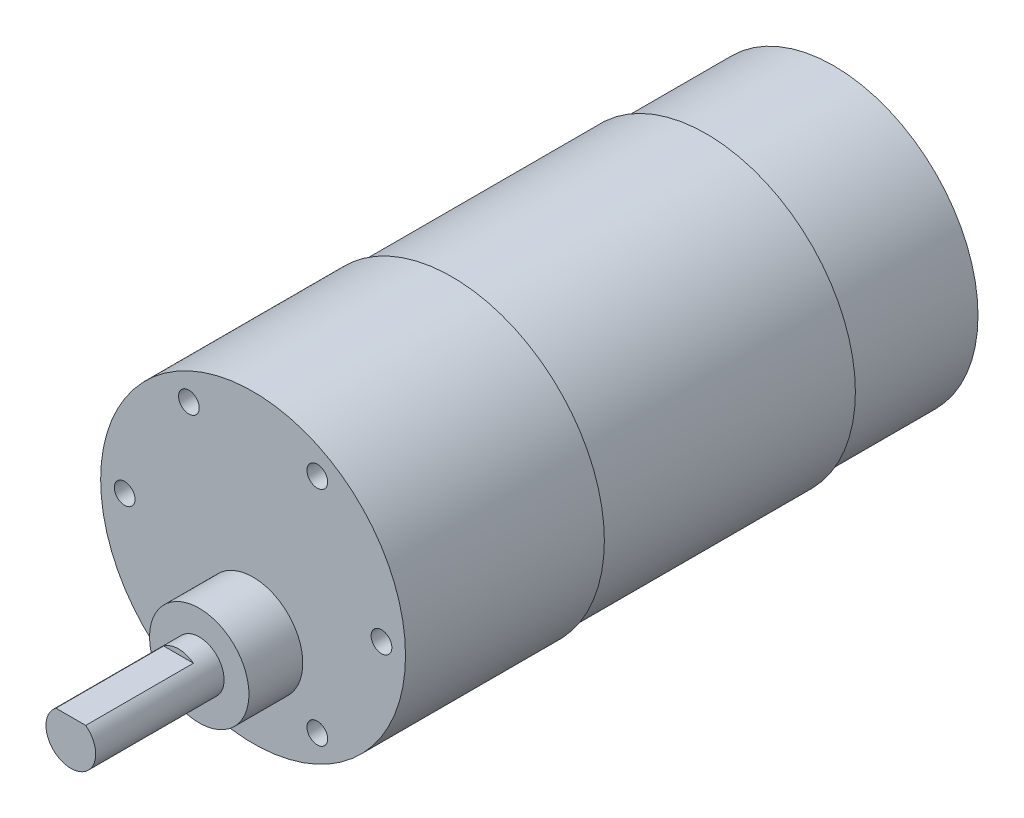
SolidWorks part; units mm, degrees
ref_plane "Front Plane" through (0, 0, 0) normal (0, 0, 1) x (1, 0, 0)
ref_plane "Top Plane" through (0, 0, 0) normal (0, 1, 0) x (1, 0, 0)
ref_plane "Right Plane" through (0, 0, 0) normal (1, 0, 0) x (0, 0, -1)
sketch "Sketch1" plane through (0, 0, 0) normal (0, 0, 1) x (1, 0, 0)
  circle A0 centre (0, 0) radius 17.4
  dimension "D1" = 34.8
extrude "Boss-Extrude1" add sketch "Sketch1" along normal blind 15.4
sketch "Sketch2" plane through (0, 0, 15.4) normal (0, 0, 1) x (1, 0, 0)
  circle A0 centre (0, 0) radius 18
  dimension "D1" = 36
extrude "Boss-Extrude2" add sketch "Sketch2" along normal blind 30.7
sketch "Sketch3" plane through (0, 0, 46.1) normal (0, 0, 1) x (1, 0, 0)
  circle A0 centre (0, 0) radius 18.4
  dimension "D1" = 36.8
extrude "Boss-Extrude3" add sketch "Sketch3" along normal blind 24
sketch "Sketch4" plane through (0, 0, 70.1) normal (0, 0, 1) x (1, 0, 0)
  circle A0 centre (0, -7) radius 6
  point P2 (0, 0)
  dimension "D2" = 12
  dimension "D1" = 7
extrude "Boss-Extrude4" add sketch "Sketch4" along normal blind 6.5
sketch "Sketch5" plane through (0, 0, 76.6) normal (0, 0, 1) x (1, 0, 0)
  circle A0 centre (0, -7) radius 3
  dimension "D1" = 6
extrude "Boss-Extrude5" add sketch "Sketch5" along normal blind 15.5
sketch "Sketch6" plane through (0, 0, 92.1) normal (0, 0, 1) x (1, 0, 0)
  line L0 (-1.8, -4.6) -> (1.8, -4.6)
  circle A0 centre (0, -7) radius 3 construction
  circle A1 centre (0, -7) radius 3 construction
  arc A2 (-1.8, -4.6) -> (1.8, -4.6) centre (0, -7) cw
  dimension "D1" = 2.4
extrude "Cut-Extrude1" cut sketch "Sketch6" against normal blind 13
hole_wizard "Tap Drill for M3x0.5 Tap1" positions "Sketch7" profile "Sketch8" hole size "M3x0.5" standard "ANSI Metric"
sketch "Sketch7" plane through (0, 0, 70.1) normal (0, 0, 1) x (1, 0, 0)
  circle A0 centre (0, 0) radius 15.5
  point P0 (-15.5, 0)
  point P13 (-7.75, 13.4234)
  point P14 (7.75, 13.4234)
  point P15 (15.5, 0)
  point P16 (7.75, -13.4234)
  point P17 (-7.75, -13.4234)
  point P24 (0, 0)
  point P25 (0, 0)
  dimension "D1" = 15.5
  dimension "D2" = 6
sketch "Sketch8" plane through (-15.5, 0, 70.1) normal (1, 0, 0) x (0, -1, 0)
  line L0 (0, 0) -> (0, 10.76)
  line L1 (0, 10.76) -> (1.25, 10.76)
  line L2 (1.25, 10.76) -> (1.25, 0)
  line L5 (1.25, 0) -> (0, 0)
  line L10 (0, 10.76) -> (-1.25, 10.76) construction
  line L11 (0, -6.35) -> (0, 107.95) construction
  dimension "Hole Dia." = 2.5
  dimension "Hole Depth" = 10.76
  dimension "Drill Angle" = 180
